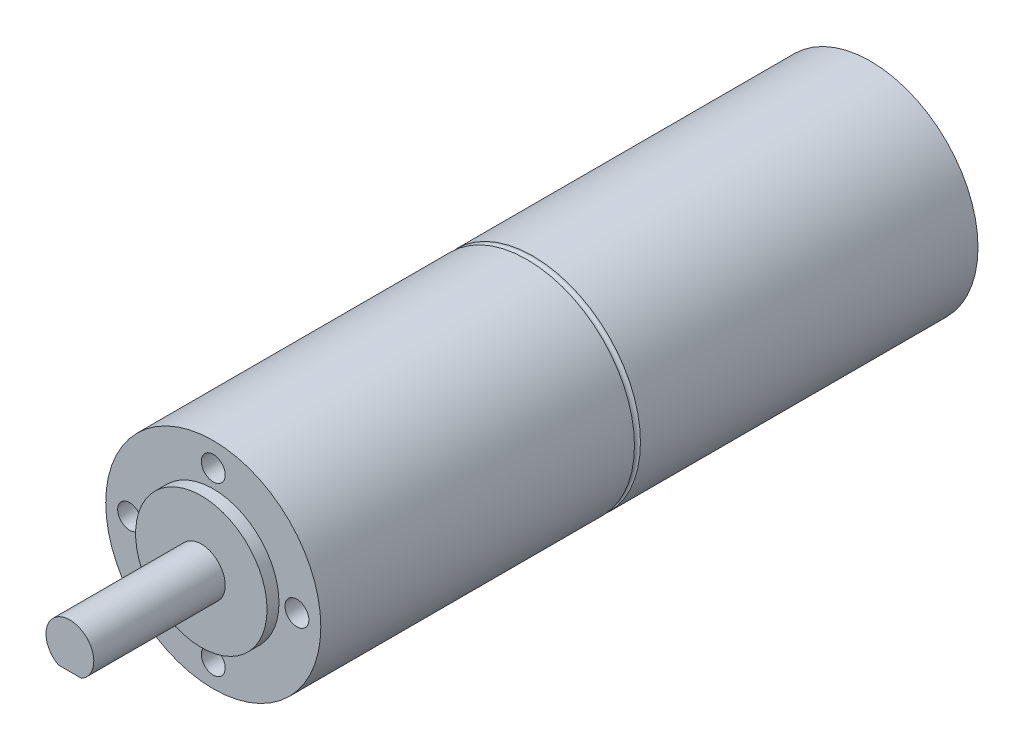
SolidWorks part; units mm, degrees
ref_plane "Front Plane" through (0, 0, 0) normal (0, 0, 1) x (1, 0, 0)
ref_plane "Top Plane" through (0, 0, 0) normal (0, 1, 0) x (1, 0, 0)
ref_plane "Right Plane" through (0, 0, 0) normal (1, 0, 0) x (0, 0, -1)
sketch "Sketch1" plane through (0, 0, 0) normal (0, 0, 1) x (1, 0, 0)
  circle A0 centre (0, 0) radius 18
  dimension "D1" = 36
extrude "Boss-Extrude1" add sketch "Sketch1" along normal blind 110
sketch "Sketch2" plane through (0, 0, 0) normal (0, 1, 0) x (1, 0, 0)
  line L0 (18, -110) -> (18, 0) construction
  line L1 (18, 0) -> (-18, 0) construction
  line L2 (0, 0) -> (0, -30.879) construction
  circle A0 centre (18, -57) radius 0.5
  dimension "D1" = 1
  dimension "D2" = 57
revolve "Cut-Revolve1" cut sketch "Sketch2" angle 360 about L2
sketch "Sketch3" plane through (0, 0, 110) normal (0, 0, 1) x (1, 0, 0)
  circle A0 centre (0, 0) radius 11
  dimension "D1" = 22
extrude "Boss-Extrude2" add sketch "Sketch3" along normal blind 2
sketch "Sketch4" plane through (0, 0, 112) normal (0, 0, 1) x (1, 0, 0)
  circle A0 centre (0, 0) radius 4
  dimension "D1" = 8
extrude "Boss-Extrude3" add sketch "Sketch4" along normal blind 22
sketch "Sketch5" plane through (0, 0, 134) normal (0, 0, 1) x (1, 0, 0)
  line L0 (-1.9365, -3.5) -> (1.9365, -3.5)
  circle A1 centre (0, 0) radius 4
  arc A2 (-1.9365, -3.5) -> (1.9365, -3.5) centre (0, 0) ccw
  dimension "D2" = 3.5
  dimension "D1" = 0
extrude "Cut-Extrude1" cut sketch "Sketch5" against normal blind 15
sketch "Sketch6" plane through (0, 0, 0) normal (0, 0, -1) x (-1, 0, 0)
  circle A0 centre (0, 0) radius 5
  dimension "D1" = 10
extrude "Boss-Extrude4" add sketch "Sketch6" along normal blind 1
sketch "Sketch7" plane through (0, 0, 110) normal (0, 0, 1) x (1, 0, 0)
  circle A0 centre (14, 0) radius 2
  circle A1 centre (0, -14) radius 2
  circle A2 centre (-14, 0) radius 2
  circle A3 centre (0, 14) radius 2
  point P12 (0, 0)
  dimension "D1" = 4
  dimension "D2" = 14
  dimension "D3" = 4
extrude "Cut-Extrude2" cut sketch "Sketch7" against normal blind 10
